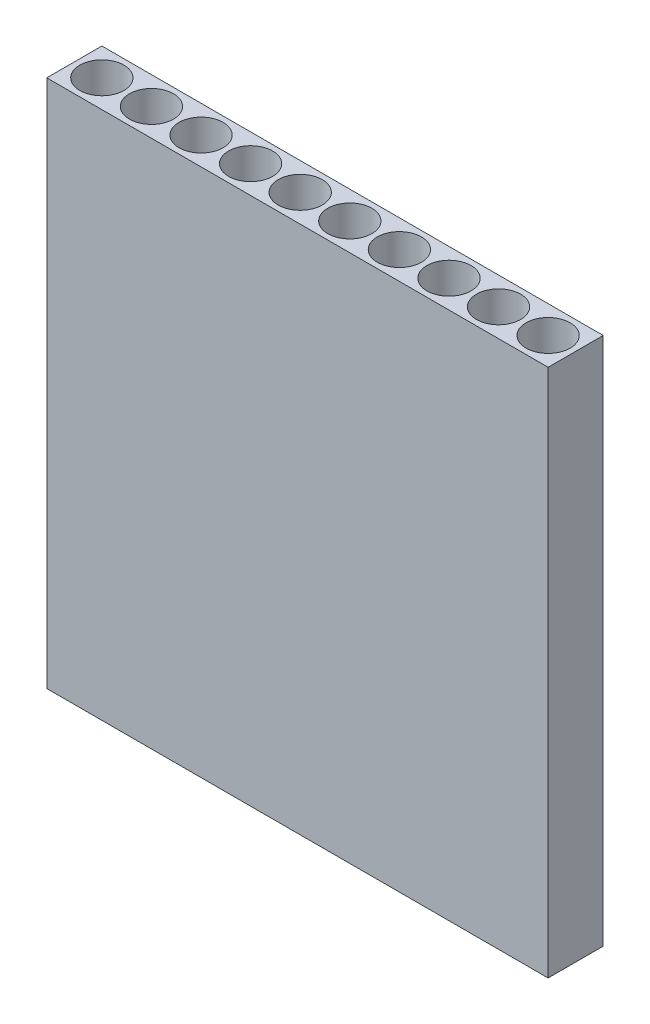
SolidWorks part; units mm, degrees
ref_plane "Front Plane" through (0, 0, 0) normal (0, 0, 1) x (1, 0, 0)
ref_plane "Top Plane" through (0, 0, 0) normal (0, 1, 0) x (1, 0, 0)
ref_plane "Right Plane" through (0, 0, 0) normal (1, 0, 0) x (0, 0, -1)
sketch "Sketch1" plane through (0, 0, 0) normal (0, 1, 0) x (1, 0, 0)
  line L0 (0, 3.175) -> (0, 3.9688) construction
  line L5 (-3.9688, 0) -> (0, 0) construction
  line L6 (-3.9688, -3.9688) -> (68.2625, -3.9688)
  line L7 (-3.9688, -3.9688) -> (-3.9688, 3.9688)
  line L8 (-3.9688, 3.9688) -> (68.2625, 3.9688)
  line L9 (68.2625, -3.9688) -> (68.2625, 3.9688)
  line L10 (0, 0) -> (0, -3.9688) construction
  line L11 (67.4688, 0) -> (68.2625, 0) construction
  line L12 (3.175, 0) -> (3.9688, 0) construction
  circle A0 centre (0, 0) radius 3.175
  circle A1 centre (7.1437, 0) radius 3.175
  circle A2 centre (14.2875, 0) radius 3.175
  circle A3 centre (21.4312, 0) radius 3.175
  circle A4 centre (28.575, 0) radius 3.175
  circle A5 centre (35.7188, 0) radius 3.175
  circle A6 centre (42.8625, 0) radius 3.175
  circle A7 centre (50.0063, 0) radius 3.175
  circle A8 centre (57.15, 0) radius 3.175
  circle A9 centre (64.2938, 0) radius 3.175
  point P0 (0, 0)
  dimension "D1" = 6.35
  dimension "D2" = 10
  dimension "D3" = 0.7937
extrude "Boss-Extrude1" add sketch "Sketch1" along normal blind 76.2
